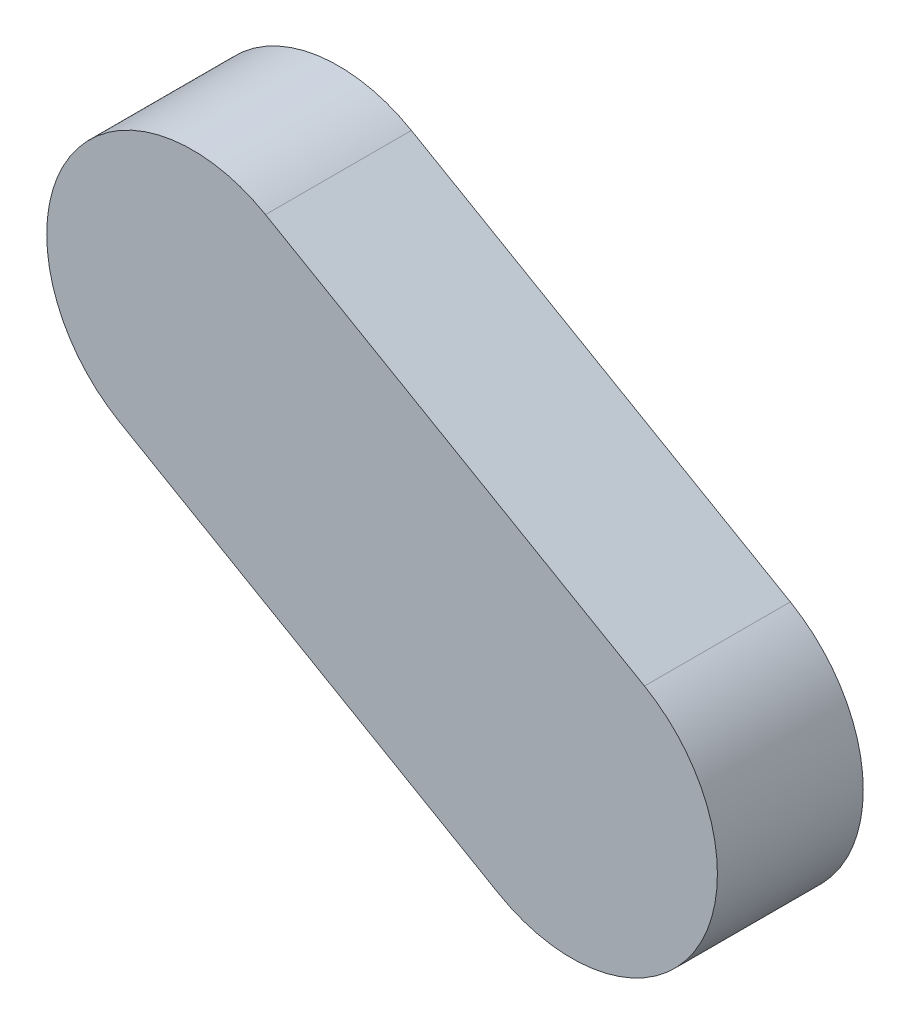
SolidWorks part; units mm, degrees
ref_plane "Alzado" through (0, 0, 0) normal (0, 0, 1) x (1, 0, 0)
ref_plane "Planta" through (0, 0, 0) normal (0, 1, 0) x (1, 0, 0)
ref_plane "Vista lateral" through (0, 0, 0) normal (1, 0, 0) x (0, 0, -1)
sketch "Croquis1" plane through (0, 0, 0) normal (0, 0, 1) x (1, 0, 0)
  line L0 (-20.9808, 23.6603) -> (5, 8.6603)
  line L1 (-30.9808, 6.3397) -> (-5, -8.6603)
  line L2 (-5, -8.6603) -> (-29.9046, -8.6603) construction
  arc A0 (-5, -8.6603) -> (5, 8.6603) centre (0, 0) ccw
  arc A1 (-20.9808, 23.6603) -> (-30.9808, 6.3397) centre (-25.9808, 15) ccw
  dimension "D1" = 30
  dimension "D2" = 20
  dimension "D3" = 30
extrude "Saliente-Extruir2" add sketch "Croquis1" along normal blind 10
